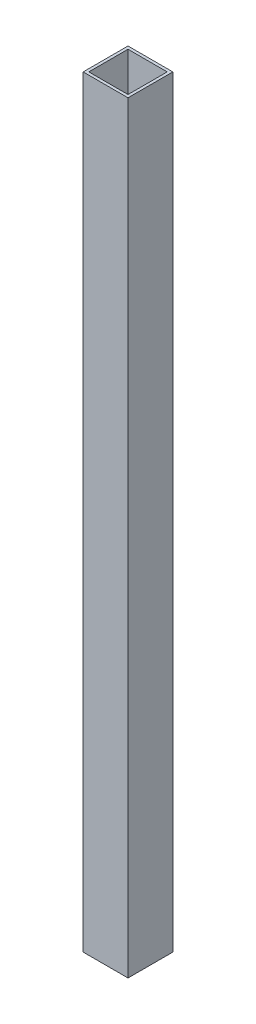
SolidWorks part; units mm, degrees
material "6061 Alloy"
ref_plane "Front Plane" through (0, 0, 0) normal (0, 0, 1) x (1, 0, 0)
ref_plane "Top Plane" through (0, 0, 0) normal (0, 1, 0) x (1, 0, 0)
ref_plane "Right Plane" through (0, 0, 0) normal (1, 0, 0) x (0, 0, -1)
sketch "Sketch1" plane through (0, 0, 0) normal (0, 1, 0) x (1, 0, 0)
  line L1 (12.7, 12.7) -> (-12.7, 12.7)
  line L2 (12.7, 12.7) -> (12.7, -12.7)
  line L3 (12.7, -12.7) -> (-12.7, -12.7)
  line L4 (-12.7, 12.7) -> (-12.7, -12.7)
  line L5 (12.7, 12.7) -> (-12.7, -12.7) construction
  line L6 (12.7, -12.7) -> (-12.7, 12.7) construction
  line L7 (11.1125, 11.1125) -> (-11.1125, 11.1125)
  line L8 (11.1125, 11.1125) -> (11.1125, -11.1125)
  line L9 (11.1125, -11.1125) -> (-11.1125, -11.1125)
  line L10 (-11.1125, 11.1125) -> (-11.1125, -11.1125)
  line L11 (11.1125, 11.1125) -> (-11.1125, -11.1125) construction
  line L12 (11.1125, -11.1125) -> (-11.1125, 11.1125) construction
  point P1 (0, 0)
  point P6 (0, 0)
  dimension "D1" = 25.4
  dimension "D2" = 25.4
  dimension "D3" = 1.5875
  dimension "D4" = 1.5875
extrude "Boss-Extrude1" add sketch "Sketch1" along normal blind 431.8
